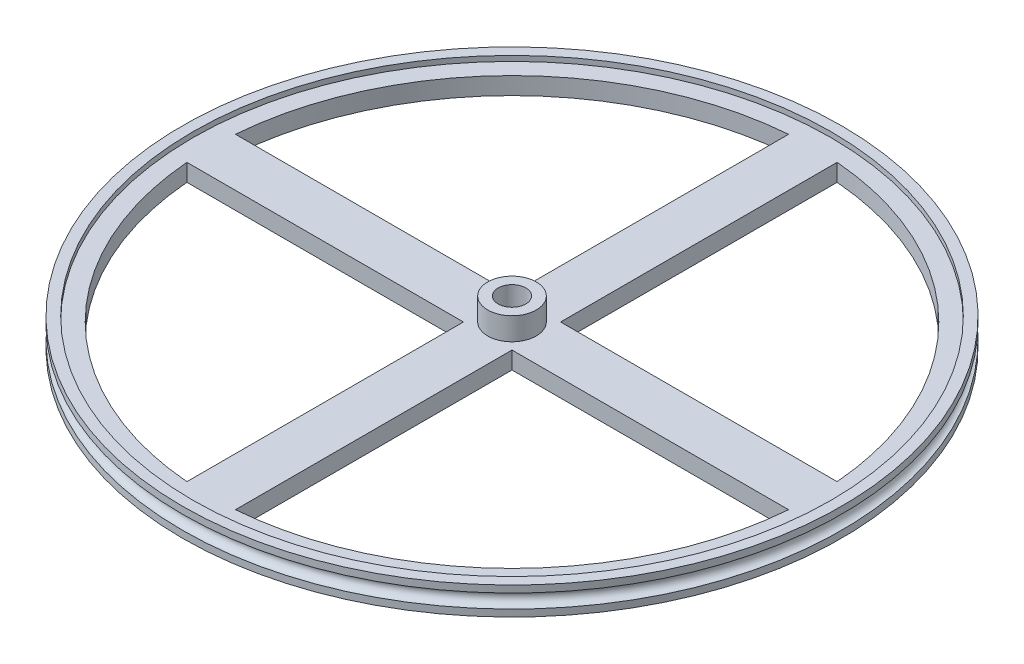
SolidWorks part; units mm, degrees
ref_plane "Front Plane" through (0, 0, 0) normal (0, 0, 1) x (1, 0, 0)
ref_plane "Top Plane" through (0, 0, 0) normal (0, 1, 0) x (1, 0, 0)
ref_plane "Right Plane" through (0, 0, 0) normal (1, 0, 0) x (0, 0, -1)
sketch "Sketch1" plane through (0, 0, 0) normal (0, 0, 1) x (1, 0, 0)
  line L0 (0, 60.3176) -> (0, -81.789) construction
  line L1 (8, 8) -> (8, -8)
  line L2 (8, 18) -> (8, 8)
  line L3 (14, -5) -> (14, -8)
  line L4 (8, -8) -> (14, -8)
  line L5 (190, 8) -> (190, 4)
  line L6 (14, 5) -> (184, 5)
  line L7 (190, -4) -> (190, -8)
  line L8 (14, -5) -> (184, -5)
  line L9 (14, 18) -> (14, 8)
  line L10 (14, 8) -> (14, 5)
  line L11 (184, 8) -> (184, 5)
  line L14 (184, 8) -> (190, 8)
  line L15 (184, -8) -> (190, -8)
  line L16 (184, -5) -> (184, -8)
  line L17 (8, 18) -> (14, 18)
  arc A0 (190, 4) -> (190, -4) centre (190, 0) ccw
  dimension "D1" = 3
  dimension "D2" = 184
  dimension "D3" = 10
  dimension "D4" = 6
  dimension "D6" = 8
  dimension "D7" = 6
revolve "Revolve2" add sketch "Sketch1" angle 360 about L0
sketch "Sketch2" plane through (0, 5, 0) normal (0, 1, 0) x (1, 0, 0)
  line L0 (14, 14) -> (14, 173.4359)
  line L1 (-173.4359, -14) -> (-14, -14)
  line L2 (-14, 14) -> (-14, 173.4359)
  line L3 (-173.4359, 14) -> (-14, 14)
  line L4 (14, 14) -> (173.4359, 14)
  line L8 (-14, -173.4359) -> (-14, -14)
  line L9 (14, -14) -> (173.4359, -14)
  line L10 (14, -173.4359) -> (14, -14)
  arc A0 (-14, 173.4359) -> (-173.4359, 14) centre (0, 0) ccw
  arc A2 (-173.4359, -14) -> (-14, -173.4359) centre (0, 0) ccw
  arc A3 (173.4359, 14) -> (14, 173.4359) centre (0, 0) ccw
  arc A4 (14, -173.4359) -> (173.4359, -14) centre (0, 0) ccw
extrude "Cut-Extrude1" cut sketch "Sketch2" against normal up to surface (10 mm away) up to face at (0, -5, 184)
